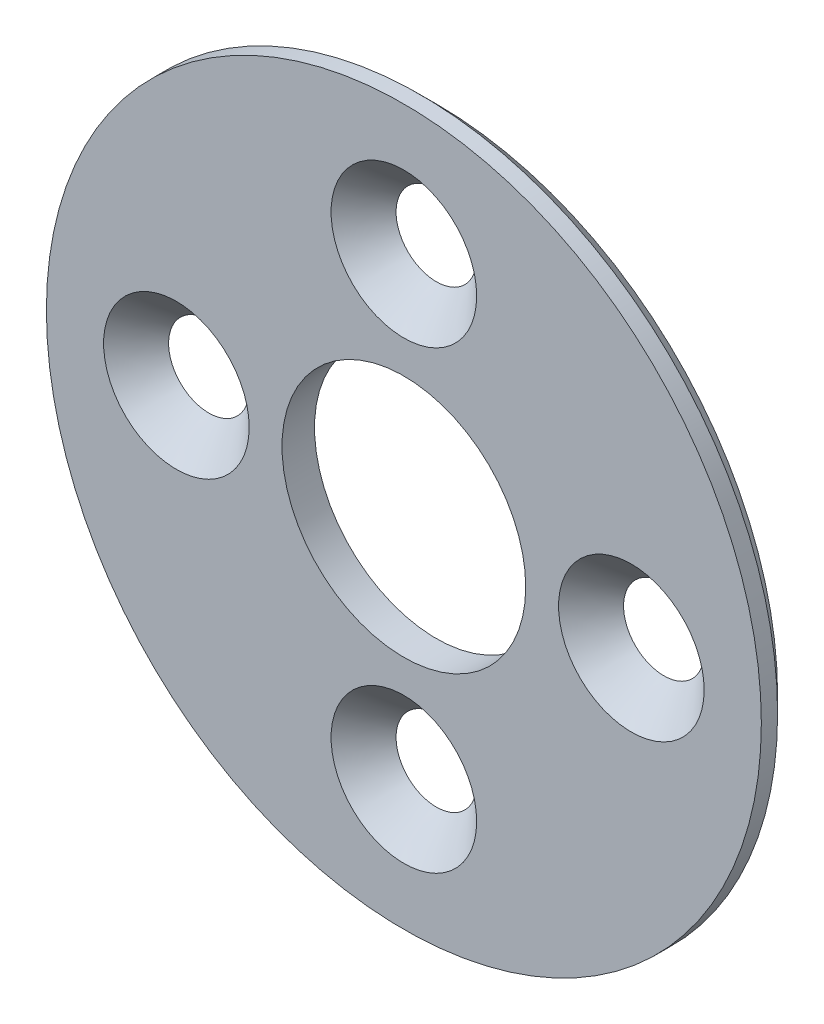
SolidWorks part; units mm, degrees
material "不锈钢"
ref_plane "前基準面" through (0, 0, 0) normal (0, 0, 1) x (1, 0, 0)
ref_plane "上基準面" through (0, 0, 0) normal (0, 1, 0) x (1, 0, 0)
ref_plane "右基準面" through (0, 0, 0) normal (1, 0, 0) x (0, 0, -1)
sketch "草图1" plane through (0, 0, 0) normal (0, 0, 1) x (1, 0, 0)
  circle A0 centre (0, 0) radius 22
  circle A1 centre (0, 0) radius 7.5
  dimension "D1" = 15
  dimension "D2" = 44
extrude "凸台-拉伸1" add sketch "草图1" along normal blind 2
chamfer "倒角1" distance 1 angle 45 1 edges at (22, 0, 0)
hole_wizard "M4 六角凹锥坑螺钉的锥形沉头孔1" positions "草图3" profile "草图2" countersink size "M4" standard "ISO" end condition through all
sketch "草图3" plane through (0, 0, 2) normal (0, 0, 1) x (1, 0, 0)
  line L0 (0, 0) -> (28.2498, 0) construction
  line L1 (0, 0) -> (0, 22.0561) construction
  line L2 (0, 0) -> (0, -24.8398) construction
  line L3 (0, 0) -> (-31.718, 0) construction
  circle A0 centre (0, 0) radius 14 construction
  point P0 (0, 14)
  point P1 (0, -14)
  point P3 (-14, 0)
  point P5 (14, 0)
  dimension "D1" = 28
sketch "草图2" plane through (0, 14, 2) normal (1, 0, 0) x (0, -1, 0)
  line L0 (0, 0) -> (0, 2)
  line L1 (0, 2) -> (2.25, 2)
  line L2 (2.25, 2) -> (2.25, 2.23)
  line L3 (2.25, 2.23) -> (4.48, 0)
  line L5 (4.48, 0) -> (0, 0)
  line L6 (-2.25, 2.23) -> (-4.48, 0) construction
  line L11 (0, -6.35) -> (0, 107.95) construction
  dimension "通孔孔直径" = 4.5
  dimension "通孔孔深度" = 2
  dimension "近端锥形沉头孔直径" = 8.96
  dimension "近端锥形沉头孔角度" = 90
